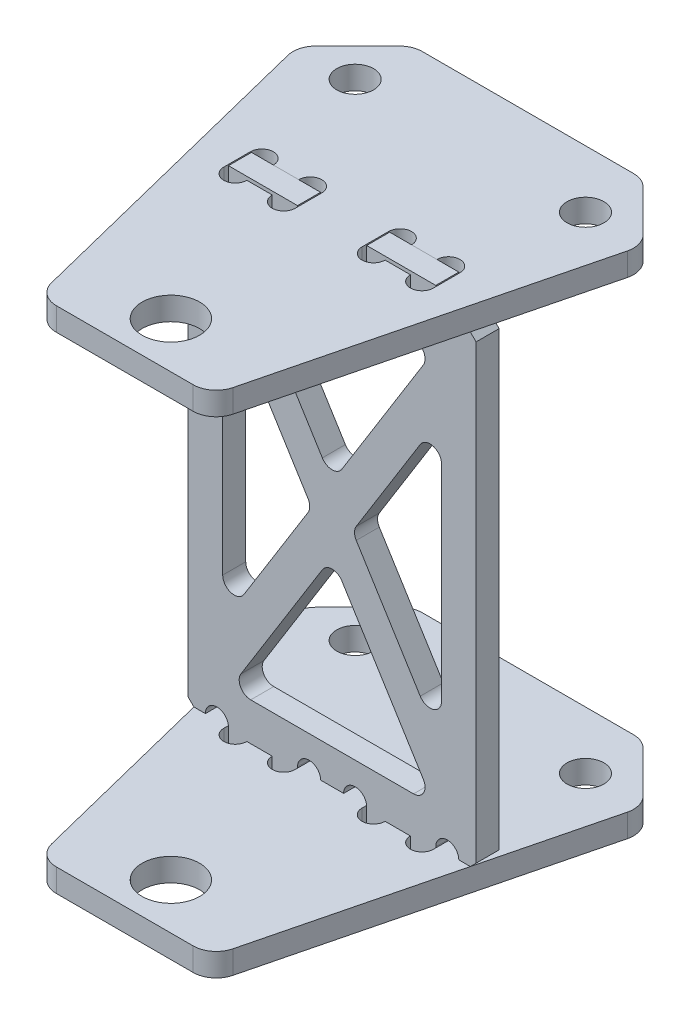
SolidWorks part; units mm, degrees
material "碳板"
ref_plane "前视基准面" through (0, 0, 0) normal (0, 0, 1) x (1, 0, 0)
ref_plane "上视基准面" through (0, 0, 0) normal (0, 1, 0) x (1, 0, 0)
ref_plane "右视基准面" through (0, 0, 0) normal (1, 0, 0) x (0, 0, -1)
sketch "草图1" plane through (0, 0, 0) normal (0, 1, 0) x (1, 0, 0)
  line L0 (0, 35.648) -> (0, -28.224) construction
  line L1 (-45.568, 0) -> (41.472, 0) construction
  line L2 (10, 5) -> (-10, 5)
  line L3 (-10, 5) -> (-15, 0)
  line L4 (-15, 0) -> (-7.5, -30)
  line L5 (-7.5, -30) -> (7.5, -30)
  line L6 (15, 0) -> (7.5, -30)
  line L7 (10, 5) -> (15, 0)
  line L8 (-4.9, -10) -> (-7.1, -10)
  line L9 (4.9, -10) -> (7.1, -10)
  line L10 (2.9, -10) -> (2.9, -12.3)
  line L11 (4.9, -12.3) -> (7.1, -12.3)
  line L12 (9.1, -10) -> (9.1, -12.3)
  line L13 (2.9, -10) -> (9.1, -12.3) construction
  line L14 (2.9, -12.3) -> (9.1, -10) construction
  line L15 (-9.1, -10) -> (-9.1, -12.3)
  line L16 (-4.9, -12.3) -> (-7.1, -12.3)
  line L17 (-2.9, -10) -> (-2.9, -12.3)
  circle A0 centre (-10, 0) radius 1.6
  circle A1 centre (10, 0) radius 1.6
  circle A3 centre (0, -26) radius 2.5
  arc A4 (4.9, -10) -> (2.9, -10) centre (3.9, -10) ccw
  arc A5 (2.9, -12.3) -> (4.9, -12.3) centre (3.9, -12.3) ccw
  arc A6 (9.1, -10) -> (7.1, -10) centre (8.1, -10) ccw
  arc A7 (7.1, -12.3) -> (9.1, -12.3) centre (8.1, -12.3) ccw
  arc A8 (-4.9, -10) -> (-2.9, -10) centre (-3.9, -10) cw
  arc A9 (-9.1, -10) -> (-7.1, -10) centre (-8.1, -10) cw
  arc A10 (-7.1, -12.3) -> (-9.1, -12.3) centre (-8.1, -12.3) cw
  arc A11 (-2.9, -12.3) -> (-4.9, -12.3) centre (-3.9, -12.3) cw
  point P1 (6, -11.15)
  point P17 (0, -30)
  point P19 (0, 5)
  point P27 (0, 0)
  point P33 (0, 0)
  point P34 (0, 0)
  dimension "D1" = 3.2
  dimension "D3" = 5
  dimension "D4" = 5
  dimension "D12" = 2
  dimension "D2" = 20
  dimension "D5" = 26
  dimension "D6" = 5
  dimension "D7" = 4
  dimension "D8" = 15
  dimension "D9" = 20
  dimension "D10" = 2.3
  dimension "D11" = 6.2
  dimension "D13" = 10
  dimension "D14" = 6
extrude "凸台-拉伸1" add sketch "草图1" along normal blind 2 from offset 20.1
fillet "圆角1" radius 2 6 edges at (-10, 21.1, -5) (10, 21.1, -5) (15, 21.1, 0) (7.5, 21.1, 30) (-15, 21.1, 0) (-7.5, 21.1, 30)
mirror "镜向2" about plane through (0, 0, 0) normal (0, 1, 0) of bodies 106
sketch "草图2" plane through (0, 0, 10) normal (0, 0, 1) x (1, 0, 0)
  line L0 (0, 44.5466) -> (0, -39.3866) construction
  line L1 (-29.1637, 0) -> (31.1157, 0) construction
  line L2 (-6, 22.1) -> (-6, 15.2832) construction
  line L3 (-4.9, 22.1) -> (-7.1, 22.1) construction
  line L4 (-9, 22.1) -> (-3, 22.1)
  line L5 (-3, 22.1) -> (-3, 20.1)
  line L6 (-1, 20.1) -> (1, 20.1)
  line L7 (-9, 22.1) -> (-9, 20.1)
  line L8 (-11, 20.1) -> (-12.5, 20.1)
  line L9 (-12.5, 20.1) -> (-12.5, -20.1)
  line L10 (12.5, 20.1) -> (12.5, -20.1)
  line L11 (11, 20.1) -> (12.5, 20.1)
  line L12 (9, 22.1) -> (9, 20.1)
  line L13 (9, 22.1) -> (3, 22.1)
  line L14 (3, 22.1) -> (3, 20.1)
  line L15 (-6, -22.1) -> (-6, -15.2832) construction
  line L16 (3, -22.1) -> (3, -20.1)
  line L17 (9, -22.1) -> (3, -22.1)
  line L18 (9, -22.1) -> (9, -20.1)
  line L19 (11, -20.1) -> (12.5, -20.1)
  line L20 (-11, -20.1) -> (-12.5, -20.1)
  line L21 (-9, -22.1) -> (-9, -20.1)
  line L22 (-1, -20.1) -> (1, -20.1)
  line L23 (-3, -22.1) -> (-3, -20.1)
  line L24 (-9, -22.1) -> (-3, -22.1)
  line L25 (-12.5, 20.1) -> (12.5, -20.1) construction
  line L26 (12.5, 20.1) -> (-12.5, -20.1) construction
  line L27 (-9.5, 12.4356) -> (-1.7664, 0)
  line L28 (8.8679, 17.1) -> (0, 2.8404)
  line L29 (-8.8679, 17.1) -> (0, 2.8404)
  line L30 (9.5, 12.4356) -> (1.7664, 0)
  line L31 (-9.5, 12.4356) -> (-9.5, -12.4356)
  line L32 (-11.2262, 20.8921) -> (13.7738, -19.3079) construction
  line L33 (-13.7738, 19.3079) -> (11.2262, -20.8921) construction
  line L34 (11.2262, 20.8921) -> (-13.7738, -19.3079) construction
  line L35 (13.7738, 19.3079) -> (-11.2262, -20.8921) construction
  line L36 (-8.8679, 17.1) -> (8.8679, 17.1)
  line L37 (-8.8679, -17.1) -> (8.8679, -17.1)
  line L38 (9.5, 12.4356) -> (9.5, -12.4356)
  line L39 (-1.7664, 0) -> (-9.5, -12.4356)
  line L40 (0, -2.8404) -> (8.8679, -17.1)
  line L41 (0, -2.8404) -> (-8.8679, -17.1)
  line L42 (1.7664, 0) -> (9.5, -12.4356)
  arc A0 (-3, 20.1) -> (-1, 20.1) centre (-2, 20.1) ccw
  arc A1 (-9, 20.1) -> (-11, 20.1) centre (-10, 20.1) cw
  arc A2 (9, 20.1) -> (11, 20.1) centre (10, 20.1) ccw
  arc A3 (3, 20.1) -> (1, 20.1) centre (2, 20.1) cw
  arc A4 (3, -20.1) -> (1, -20.1) centre (2, -20.1) ccw
  arc A5 (9, -20.1) -> (11, -20.1) centre (10, -20.1) cw
  arc A6 (-9, -20.1) -> (-11, -20.1) centre (-10, -20.1) ccw
  arc A7 (-3, -20.1) -> (-1, -20.1) centre (-2, -20.1) cw
  point P30 (0, 20.1)
  point P47 (12.5, 0)
  point P48 (-12.5, 0)
  point P50 (0, -20.1)
  dimension "D1" = 1
  dimension "D2" = 3
  dimension "D3" = 2
  dimension "D4" = 1.5
  dimension "D7" = 3
  dimension "D8" = 3
  dimension "D6" = 1.5
extrude "凸台-拉伸2" add sketch "草图2" along normal blind 2 separate body
fillet "圆角2" radius 1 12 edges at (9.5, 12.4356, 11) (1.7664, 0, 11) (9.5, -12.4356, 11) (8.8679, -17.1, 11) (0, -2.8404, 11) (-8.8679, -17.1, 11) (-1.7664, 0, 11) (8.8679, 17.1, 11) (-8.8679, 17.1, 11) (0, 2.8404, 11) (-9.5, -12.4356, 11) (-9.5, 12.4356, 11)
chamfer "倒角1" distance 0.5 angle 45 4 edges at (-12.5, -20.1, 11) (12.5, -20.1, 11) (12.5, 20.1, 11) (-12.5, 20.1, 11)
